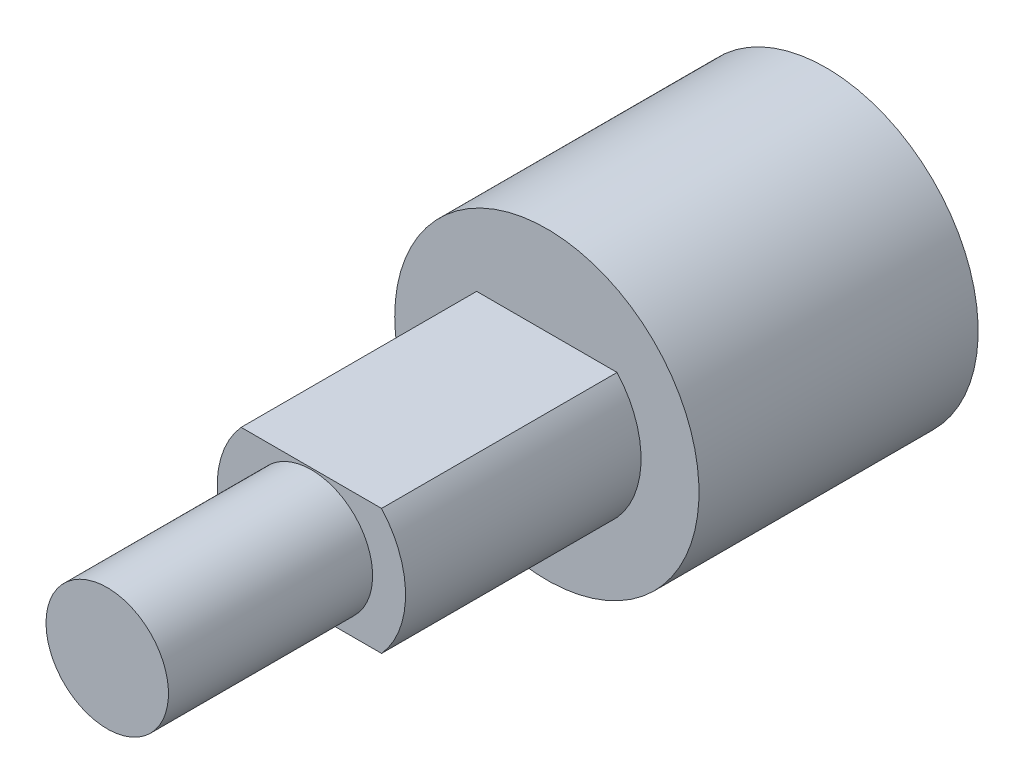
SolidWorks part; units mm, degrees
ref_plane "Front Plane" through (0, 0, 0) normal (0, 0, 1) x (1, 0, 0)
ref_plane "Top Plane" through (0, 0, 0) normal (0, 1, 0) x (1, 0, 0)
ref_plane "Right Plane" through (0, 0, 0) normal (1, 0, 0) x (0, 0, -1)
sketch "Sketch1" plane through (0, 0, 0) normal (0, 0, 1) x (1, 0, 0)
  circle A0 centre (0, 0) radius 4.845
  circle A1 centre (0, 0) radius 1.5
  dimension "D1" = 9.69
  dimension "D2" = 3
extrude "Boss-Extrude1" add sketch "Sketch1" along normal blind 8.89
sketch "Sketch2" plane through (0, 0, 8.89) normal (0, 0, 1) x (1, 0, 0)
  line L0 (-2.2361, 2) -> (2.2361, 2)
  line L1 (-2.2361, -2) -> (2.2361, -2)
  arc A1 (-2.2361, 2) -> (-2.2361, -2) centre (0, 0) ccw
  circle A2 centre (0, 0) radius 1.5
  circle A3 centre (0, 0) radius 1.5
  arc A4 (2.2361, -2) -> (2.2361, 2) centre (0, 0) ccw
  dimension "D2" = 6
  dimension "D3" = 2
  dimension "D4" = 2
  dimension "D1" = 0
extrude "Boss-Extrude2" add sketch "Sketch2" along normal blind 7.5
sketch "Sketch3" plane through (0, 0, 16.39) normal (0, 0, 1) x (1, 0, 0)
  circle A0 centre (0, 0) radius 1.95
  dimension "D1" = 3.9
extrude "Boss-Extrude3" add sketch "Sketch3" along normal blind 6.5
